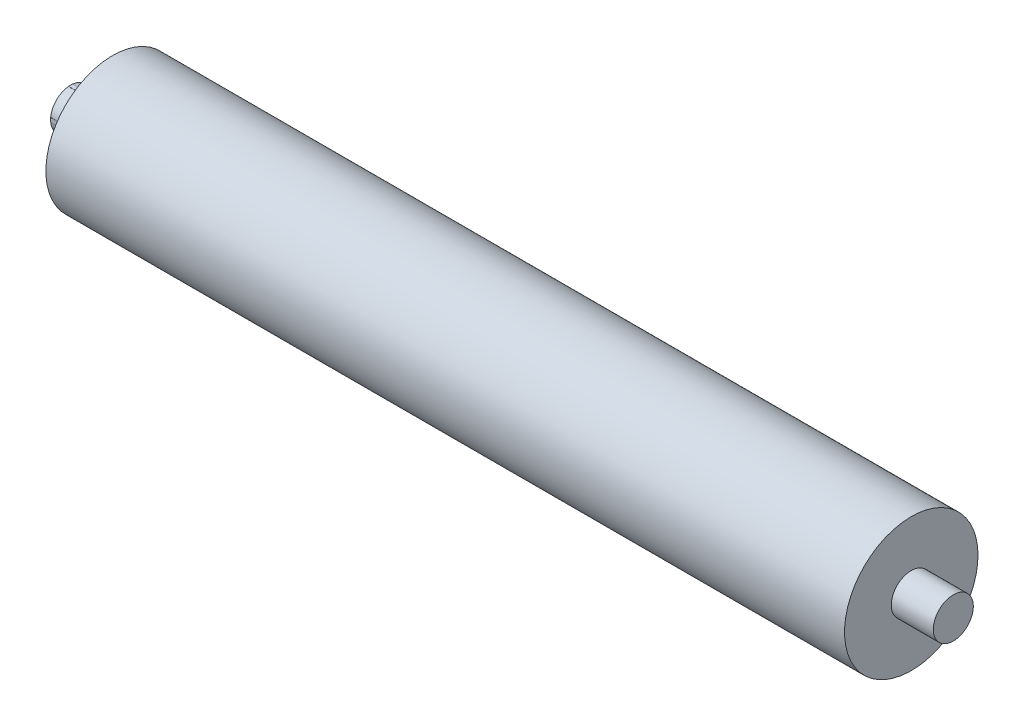
SolidWorks part; units mm, degrees
ref_plane "Alzado" through (0, 0, 0) normal (0, 0, 1) x (1, 0, 0)
ref_plane "Planta" through (0, 0, 0) normal (0, 1, 0) x (1, 0, 0)
ref_plane "Vista lateral" through (0, 0, 0) normal (1, 0, 0) x (0, 0, -1)
sketch "Croquis1" plane through (0, 0, 0) normal (1, 0, 0) x (0, 0, -1)
  circle A0 centre (0, 0) radius 9.525
  dimension "D1" = 19.05
extrude "Saliente-Extruir1" add sketch "Croquis1" along normal blind 20
sketch "Croquis2" plane through (20, 0, 0) normal (1, 0, 0) x (0, 0, -1)
  circle A0 centre (0, 0) radius 31.75
  dimension "D1" = 63.5
extrude "Saliente-Extruir2" add sketch "Croquis2" along normal blind 380
sketch "Croquis3" plane through (400, 0, 0) normal (1, 0, 0) x (0, 0, -1)
  circle A0 centre (0, 0) radius 9.525
extrude "Saliente-Extruir3" add sketch "Croquis3" along normal blind 20
sketch "Croquis4" plane through (0, 0, 0) normal (-1, 0, 0) x (0, 0, 1)
  line L0 (0, 9.525) -> (-1, 9.525)
  line L1 (-1, 9.525) -> (-1, 8.525)
  line L2 (-1, 8.525) -> (1, 8.525)
  line L3 (1, 8.525) -> (1, 9.525)
  line L4 (1, 9.525) -> (0, 9.525)
  line L5 (9.525, 0) -> (9.525, 1)
  line L6 (9.525, 1) -> (8.525, 1)
  line L7 (8.525, 1) -> (8.525, -1)
  line L8 (8.525, -1) -> (9.525, -1)
  line L9 (9.525, -1) -> (9.525, 0)
  circle A0 centre (0, 0) radius 9.525 construction
  circle A1 centre (0, 0) radius 9.525 construction
  dimension "D1" = 1
  dimension "D2" = 1
  dimension "D3" = 1
  dimension "D4" = 1
  dimension "D5" = 1
  dimension "D6" = 1
extrude "Saliente-Extruir4" add sketch "Croquis4" against normal up to surface (20 mm away) up to face at (20, 0, -9.525)
